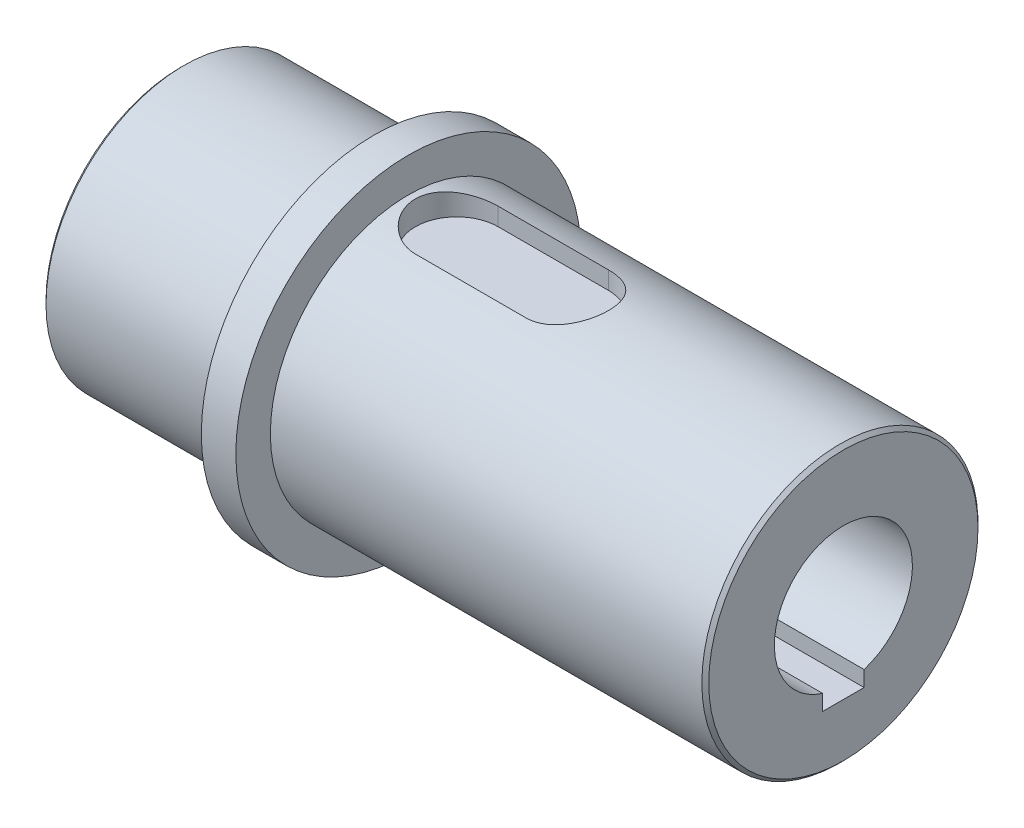
SolidWorks part; units mm, degrees
ref_plane "Front Plane" through (0, 0, 0) normal (0, 0, 1) x (1, 0, 0)
ref_plane "Top Plane" through (0, 0, 0) normal (0, 1, 0) x (1, 0, 0)
ref_plane "Right Plane" through (0, 0, 0) normal (1, 0, 0) x (0, 0, -1)
sketch "Sketch1" plane through (0, 0, 0) normal (0, 1, 0) x (1, 0, 0)
  line L0 (0, 0) -> (96, 0) construction
  line L1 (96, 0) -> (96, 19.5)
  line L2 (95.5, 20) -> (33, 20)
  line L3 (33, 20) -> (33, 25)
  line L4 (33, 25) -> (28, 25)
  line L5 (28, 25) -> (28, 20)
  line L6 (28, 20) -> (0.5, 20)
  line L7 (0, 19.5) -> (0, 0)
  line L8 (0.5, 20) -> (0, 19.5)
  line L9 (96, 19.5) -> (95.5, 20)
  line L10 (0, 0) -> (96, 0)
  point P4 (96, 20)
  point P9 (0, 20)
  dimension "D1" = 96
  dimension "D2" = 63
  dimension "D3" = 5
  dimension "D4" = 40
  dimension "D5" = 40
  dimension "D6" = 50
revolve "Revolve1" add sketch "Sketch1" angle 360 about L0
ref_plane "Plane1" through (0, 20, 0) normal (0, 1, 0) x (1, 0, 0)
sketch "Sketch2" plane through (0, 20, 0) normal (0, 1, 0) x (1, 0, 0)
  line L0 (40, 0) -> (56, 0) construction
  line L1 (40, 6) -> (56, 6)
  line L2 (40, -6) -> (56, -6)
  line L3 (33, -25) -> (33, 25) construction
  arc A0 (40, 6) -> (40, -6) centre (40, 0) ccw
  arc A1 (56, -6) -> (56, 6) centre (56, 0) ccw
  point P3 (48, 0)
  dimension "D1" = 16
  dimension "D2" = 12
  dimension "D3" = 7
extrude "Cut-Extrude1" cut sketch "Sketch2" against normal blind 3.5
sketch "Sketch3" plane through (0, 0, 0) normal (-1, 0, 0) x (0, 0, 1)
  circle A0 centre (0, 0) radius 10
extrude "Cut-Extrude2" cut sketch "Sketch3" against normal through all
sketch "Sketch4" plane through (0, 0, 0) normal (-1, 0, 0) x (0, 0, 1)
  line L0 (0, 0) -> (0, 10) construction
  line L1 (-3, -8.719) -> (3, -8.719)
  line L2 (-3, -8.719) -> (-3, -11.8)
  line L3 (-3, -11.8) -> (3, -11.8)
  line L4 (3, -8.719) -> (3, -11.8)
  circle A0 centre (0, 0) radius 10 construction
  point P4 (0, -8.719)
  dimension "D1" = 21.8
  dimension "D2" = 6
  dimension "D3" = 3
extrude "Cut-Extrude3" cut sketch "Sketch4" against normal through all
